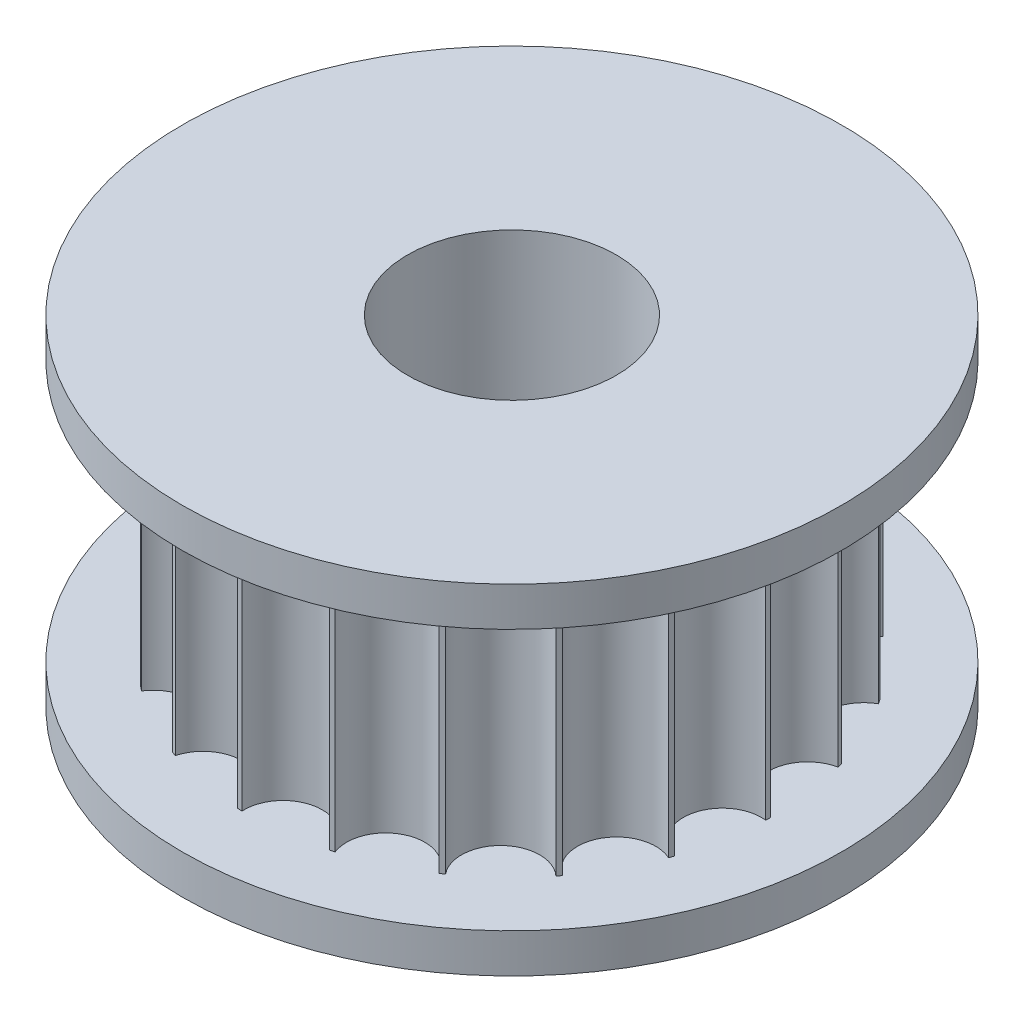
SolidWorks part; units mm, degrees
ref_plane "前视基准面" through (0, 0, 0) normal (0, 0, 1) x (1, 0, 0)
ref_plane "上视基准面" through (0, 0, 0) normal (0, 1, 0) x (1, 0, 0)
ref_plane "右视基准面" through (0, 0, 0) normal (1, 0, 0) x (0, 0, -1)
sketch "草图1" plane through (0, 0, 0) normal (1, 0, 0) x (0, 0, -1)
  line L0 (0, 33.2417) -> (0, -24.8245)
  line L1 (0, 17.0505) -> (-12.625, 17.0505)
  line L2 (-12.625, 17.0505) -> (-12.625, 15.5505)
  line L3 (-12.625, 15.5505) -> (-10.125, 15.5505)
  line L4 (-10.125, 15.5505) -> (-10.125, 5.5505)
  line L5 (-10.125, 5.5505) -> (-12.625, 5.5505)
  line L6 (-12.625, 5.5505) -> (-12.625, 4.0505)
  line L7 (-12.625, 4.0505) -> (0, 4.0505)
  point P5 (-12.625, 16.3005)
  dimension "D1" = 10.125
  dimension "D2" = 2.5
  dimension "D3" = 1.5
  dimension "D4" = 1.5
  dimension "D5" = 4.0505
  dimension "D6" = 10
revolve "旋转1" add sketch "草图1" angle 360 about L0
sketch "草图2" plane through (0, 15.5505, 0) normal (0, -1, 0) x (1, 0, 0)
  circle A0 centre (0, 0) radius 10.125 construction
  circle A1 centre (0, 0) radius 10.125
  circle A2 centre (-10.0436, 1.281) radius 1.5
  circle M1 centre (0, 0) radius 10.125
  dimension "D1" = 3
extrude "切除-拉伸3" cut sketch "草图2" along normal up to surface (10 mm away) contours A2 M1 | A2 M1
pattern_circular "阵列(圆周)2" count 20 over 360 about axis through (0, 0, 0) along (0, 1, 0) of "切除-拉伸3"
sketch "草图3" plane through (0, 4.0505, 0) normal (0, -1, 0) x (1, 0, 0)
  circle A0 centre (0, 0) radius 4
  dimension "D1" = 8
extrude "切除-拉伸4" cut sketch "草图3" against normal through all
